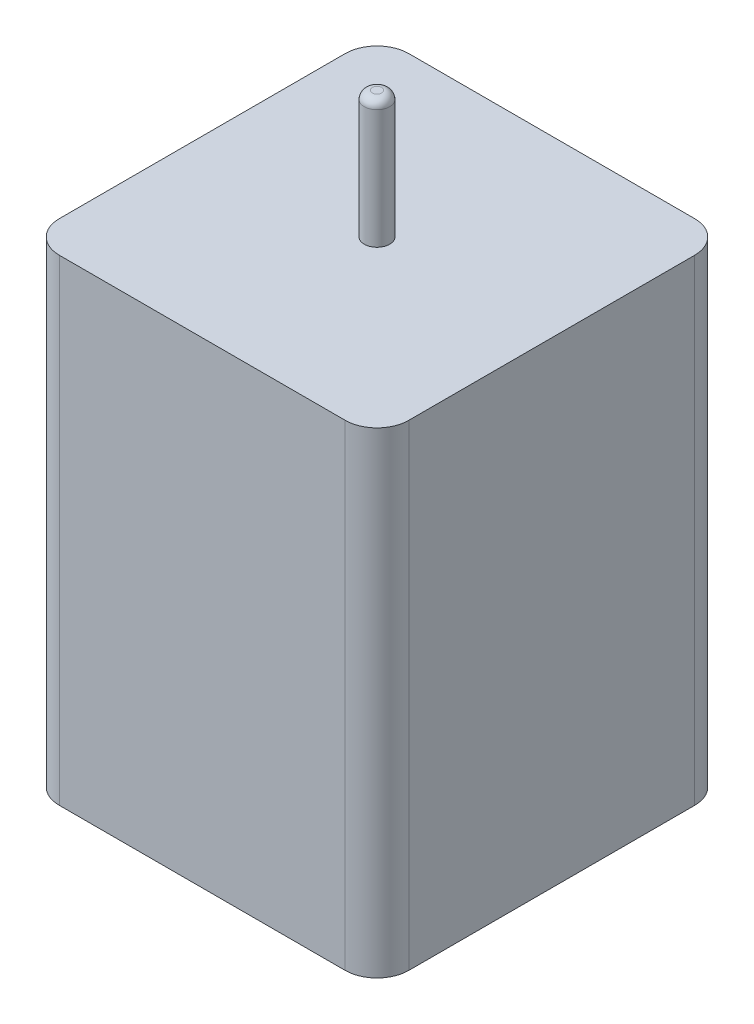
SolidWorks part; units mm, degrees
ref_plane "Front Plane" through (0, 0, 0) normal (0, 0, 1) x (1, 0, 0)
ref_plane "Top Plane" through (0, 0, 0) normal (0, 1, 0) x (1, 0, 0)
ref_plane "Right Plane" through (0, 0, 0) normal (1, 0, 0) x (0, 0, -1)
sketch "Sketch1" plane through (0, 0, 0) normal (0, 1, 0) x (1, 0, 0)
  line L1 (110, 110) -> (-110, 110)
  line L2 (110, 110) -> (110, -110)
  line L3 (110, -110) -> (-110, -110)
  line L4 (-110, 110) -> (-110, -110)
  line L5 (110, 110) -> (-110, -110) construction
  line L6 (110, -110) -> (-110, 110) construction
  point P0 (0, 0)
  dimension "D1" = 220
  dimension "D2" = 220
extrude "Boss-Extrude1" add sketch "Sketch1" along normal blind 300
sketch "Sketch2" plane through (0, 300, 0) normal (0, 1, 0) x (1, 0, 0)
  circle A0 centre (0, 0) radius 8
  dimension "D1" = 16
extrude "Boss-Extrude2" add sketch "Sketch2" along normal blind 80
fillet "Fillet1" radius 20 4 edges at (-110, 150, -110) (110, 150, -110) (110, 150, 110) (-110, 150, 110)
fillet "Fillet2" radius 5 1 edges at (0, 380, 8)
